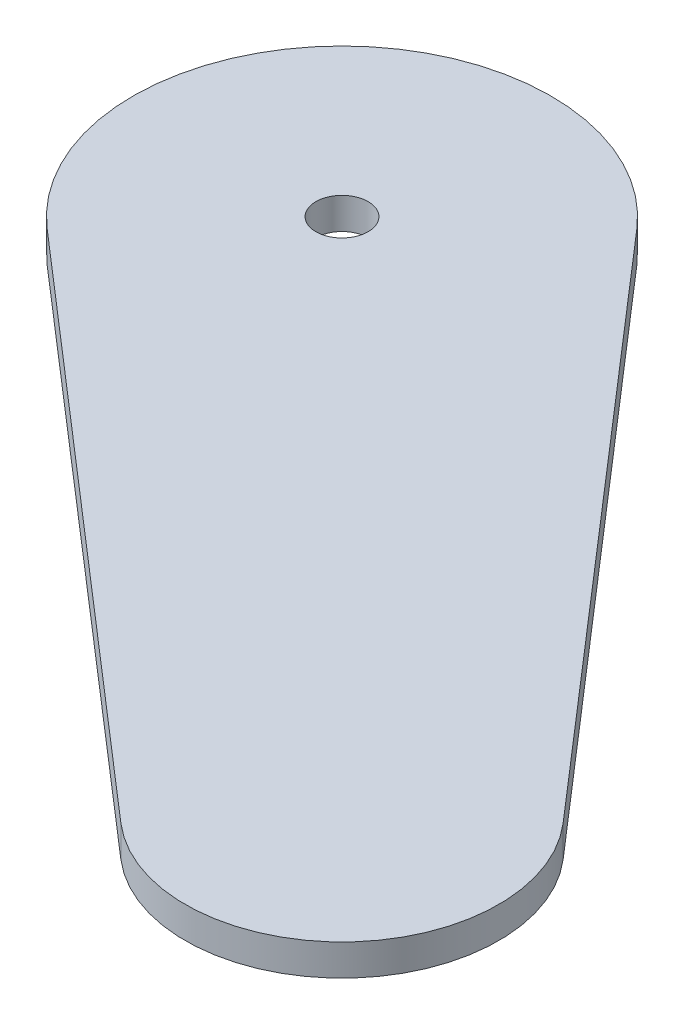
SolidWorks part; units mm, degrees
ref_plane "前视基准面" through (0, 0, 0) normal (0, 0, 1) x (1, 0, 0)
ref_plane "上视基准面" through (0, 0, 0) normal (0, 1, 0) x (1, 0, 0)
ref_plane "右视基准面" through (0, 0, 0) normal (1, 0, 0) x (0, 0, -1)
other "Configuration Table"
sketch "草图1" plane through (0, 0, 0) normal (0, 1, 0) x (1, 0, 0)
  line L0 (0, 0) -> (35.275, 0) construction
  line L1 (0, 0) -> (49.4975, -49.4975) construction
  line L2 (-13.0959, -15.1162) -> (39.6756, -60.8346)
  line L3 (15.1162, 13.0959) -> (60.8346, -39.6756)
  circle A0 centre (0, 0) radius 20
  circle A1 centre (49.4975, -49.4975) radius 15
  dimension "D1" = 40
  dimension "D3" = 30
  dimension "D2" = 70
extrude "凸台-拉伸1" add sketch "草图1" along normal blind 3 contours A0 | A1 L3 A0 L2 | A1
sketch "草图2" plane through (0, 3, 0) normal (0, 1, 0) x (1, 0, 0)
  circle A0 centre (0, 0) radius 2.5
  dimension "D1" = 5
extrude "切除-拉伸1" cut sketch "草图2" against normal through all
